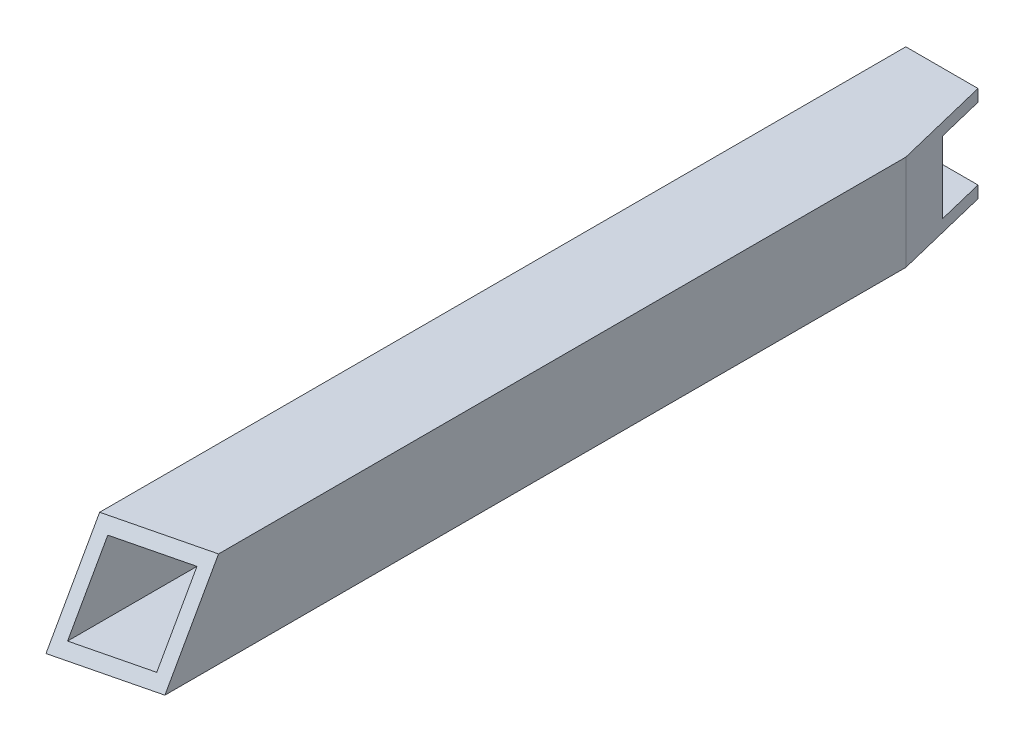
SolidWorks part; units mm, degrees
material "6061 Alloy"
ref_plane "Front Plane" through (0, 0, 0) normal (0, 0, 1) x (1, 0, 0)
ref_plane "Top Plane" through (0, 0, 0) normal (0, 1, 0) x (1, 0, 0)
ref_plane "Right Plane" through (0, 0, 0) normal (1, 0, 0) x (0, 0, -1)
sketch "Sketch1" plane through (0, 0, 0) normal (0, 0, 1) x (1, 0, 0)
  line L0 (12.7, 0) -> (9.525, 0) construction
  line L1 (-12.7, 0) -> (12.7, 0) construction
  line L2 (0, 12.7) -> (0, -12.7)
  point P7 (0, 0)
sketch "Sketch2" plane through (0, 0, 0) normal (1, 0, 0) x (0, 0, -1)
  line L0 (114.3, 0) -> (-114.3, 0)
  point P4 (0, 0)
  dimension "Length" = 228.6
sketch "Sketch3" plane through (0, 0, 0) normal (0, 0, 1) x (1, 0, 0)
  line L0 (-12.7, 0) -> (12.7, 0) construction
  line L5 (12.7, -12.7) -> (-12.7, -12.7)
  line L6 (12.7, -12.7) -> (12.7, 12.7)
  line L11 (12.7, 12.7) -> (-12.7, 12.7)
  line L12 (-12.7, -12.7) -> (-12.7, 12.7)
  line L14 (12.7, -12.7) -> (-12.7, 12.7) construction
  line L15 (12.7, 12.7) -> (-12.7, -12.7) construction
  line L16 (9.525, -9.525) -> (-9.525, -9.525)
  line L17 (9.525, -9.525) -> (9.525, 9.525)
  line L18 (9.525, 9.525) -> (-9.525, 9.525)
  line L19 (-9.525, -9.525) -> (-9.525, 9.525)
  line L20 (9.525, -9.525) -> (-9.525, 9.525) construction
  line L21 (9.525, 9.525) -> (-9.525, -9.525) construction
  point P0 (0, 0)
  point P5 (0, 0)
  point P13 (9.525, -12.7)
  dimension "D1" = 3.175
  dimension "D3" = 25.4
  dimension "D4" = 25.4
extrude "Boss-Extrude1" add sketch "Sketch3" along normal up to vertex (114.3 mm away) and the other way up to vertex (114.3 mm away) up to point (0, 0, 114.3) other way up to point (0, 0, -114.3)
sketch "Sketch5" plane through (0, 0, 0) normal (1, 0, 0) x (0, 0, -1)
  line L0 (-114.3, 0) -> (114.3, 0) construction
  line L3 (-114.3, -12.7) -> (-114.3, 12.7) construction
  line L4 (114.3, -12.7) -> (114.3, 12.7) construction
  point P6 (-85.725, 0)
  point P7 (-76.2, 0)
  point P8 (76.2, 0)
  point P10 (85.725, 0)
  dimension "D1" = 28.575
  dimension "D2" = 38.1
  dimension "D3" = 28.575
  dimension "D4" = 38.1
sketch "Sketch7" plane through (0, -12.7, 0) normal (0, -1, 0) x (1, 0, 0)
  line L0 (-12.7, 114.3) -> (12.7, 108.0884) construction
  line L1 (12.7, 114.3) -> (12.7, -114.3) construction
  line L2 (-12.7, 114.3) -> (12.7, 114.3) construction
  dimension "D1" = 13.742
ref_plane "Plane2" through (25.6581, 0, 104.9195) normal (0.2376, 0, 0.9714) x (0, -1, 0)
ref_plane "Plane3" through (18.5067, 42.4935, 75.6763) normal (0.2085, 0.4788, 0.8528) x (0.9714, 0, -0.2376)
other "SurfaceCut2"
sketch "Sketch8" plane through (0, -12.7, 0) normal (0, -1, 0) x (1, 0, 0)
  line L0 (12.7, -88.9) -> (6.4884, -114.3) construction
  line L1 (12.7, 108.0884) -> (12.7, -114.3) construction
  line L2 (-12.7, -114.3) -> (12.7, -114.3) construction
  dimension "D1" = 13.742
  dimension "D2" = 25.4
sketch "Sketch9" plane through (0, 0, -114.3) normal (0, 0, -1) x (-1, 0, 0)
  line L0 (-6.4884, -12.7) -> (-6.4884, 12.7) construction
  line L1 (-12.7, 12.7) -> (12.7, 12.7) construction
ref_plane "Plane4" through (32.4971, 0, -7.9472) normal (0.9714, 0, -0.2376) x (0, 1, 0)
other "SurfaceCut4"
equation "\"D1@Sketch3\"=\"Wall thickness@Sketch1\""
equation "\"D1@Sketch5\"=\"Width@Sketch1\"*1.125"
equation "\"D2@Sketch5\"=\"Width@Sketch1\"*1.5"
equation "\"D3@Sketch5\"=\"D1@Sketch5\""
equation "\"D4@Sketch5\"=\"D2@Sketch5\""
equation "\"D2@Sketch3\"=\"Wall Thickness@Sketch1\""
